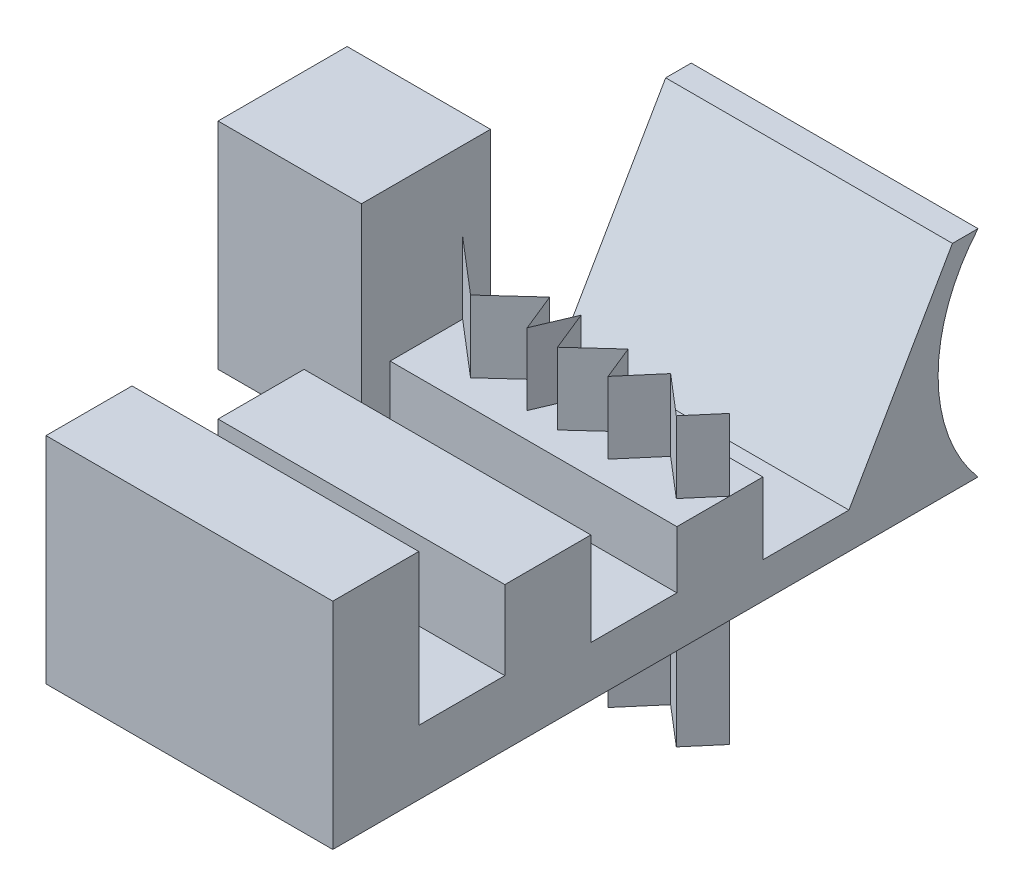
SolidWorks part; units mm, degrees
material "AISI 1020"
ref_plane "Front Plane" through (0, 0, 0) normal (0, 0, 1) x (1, 0, 0)
ref_plane "Top Plane" through (0, 0, 0) normal (0, 1, 0) x (1, 0, 0)
ref_plane "Right Plane" through (0, 0, 0) normal (1, 0, 0) x (0, 0, -1)
sketch "Sketch1" plane through (0, 0, 0) normal (1, 0, 0) x (0, 0, -1)
  line L0 (0, 0) -> (0, 150)
  line L1 (0, 150) -> (60, 150)
  line L2 (60, 150) -> (60, 45)
  line L3 (60, 45) -> (120, 45)
  line L4 (120, 45) -> (120, 100)
  line L5 (120, 100) -> (180, 100)
  line L6 (180, 100) -> (180, 35)
  line L7 (180, 35) -> (240, 35)
  line L8 (240, 35) -> (240, 75)
  line L9 (240, 75) -> (300, 75)
  line L10 (300, 75) -> (300, 25)
  line L11 (300, 25) -> (360, 25)
  line L12 (360, 25) -> (432.1688, 150)
  line L13 (432.1688, 150) -> (450, 150)
  line L14 (450, 150) -> (450, 0) construction
  line L15 (450, 0) -> (0, 0)
  arc A0 (450, 150) -> (450, 0) centre (537.178, 75) ccw
  dimension "D1" = 150
  dimension "D6" = 115
  dimension "D2" = 450
  dimension "D3" = 45
  dimension "D4" = 35
  dimension "D5" = 25
  dimension "D7" = 60
  dimension "D8" = 60
  dimension "D9" = 100
  dimension "D10" = 75
extrude "Boss-Extrude1" add sketch "Sketch1" along normal mid plane 200
sketch "Sketch2" plane through (0, 0, 0) normal (0, -1, 0) x (1, 0, 0)
  line L1 (-230, -250) -> (-130, -250)
  line L2 (-230, -250) -> (-230, -340)
  line L3 (-230, -340) -> (-130, -340)
  line L4 (-130, -250) -> (-130, -340)
  line L5 (100, 0) -> (-100, 0) construction
  line L6 (-100, 0) -> (-100, -450) construction
  dimension "D1" = 30
  dimension "D2" = 90
  dimension "D3" = 100
  dimension "D4" = 250
extrude "Boss-Extrude2" add sketch "Sketch2" against normal blind 150 separate body
sketch "Sketch3" plane through (0, 75, 0) normal (0, 1, 0) x (1, 0, 0)
  line L0 (-100, 290.5855) -> (-61.8619, 257.9496)
  line L1 (-100, 300) -> (-100, 240) construction
  line L2 (-61.8619, 257.9496) -> (-32.9918, 284.3093)
  line L3 (-32.9918, 284.3093) -> (-22.3224, 257.9496)
  line L4 (-22.3224, 257.9496) -> (-11.153, 284.3093)
  line L5 (-11.153, 284.3093) -> (0, 256.7548)
  line L6 (0, 256.7548) -> (25.744, 280.2602)
  line L7 (25.744, 280.2602) -> (35.2581, 256.7548)
  line L8 (35.2581, 256.7548) -> (55.3724, 280.2602)
  line L9 (55.3724, 280.2602) -> (82.8407, 256.7548)
  line L10 (82.8407, 256.7548) -> (100, 276.807)
  line L11 (100, 300) -> (100, 240) construction
surface "Surface-Extrude1" sketch "Sketch3" parameters "D1"=50, "D2"=150
